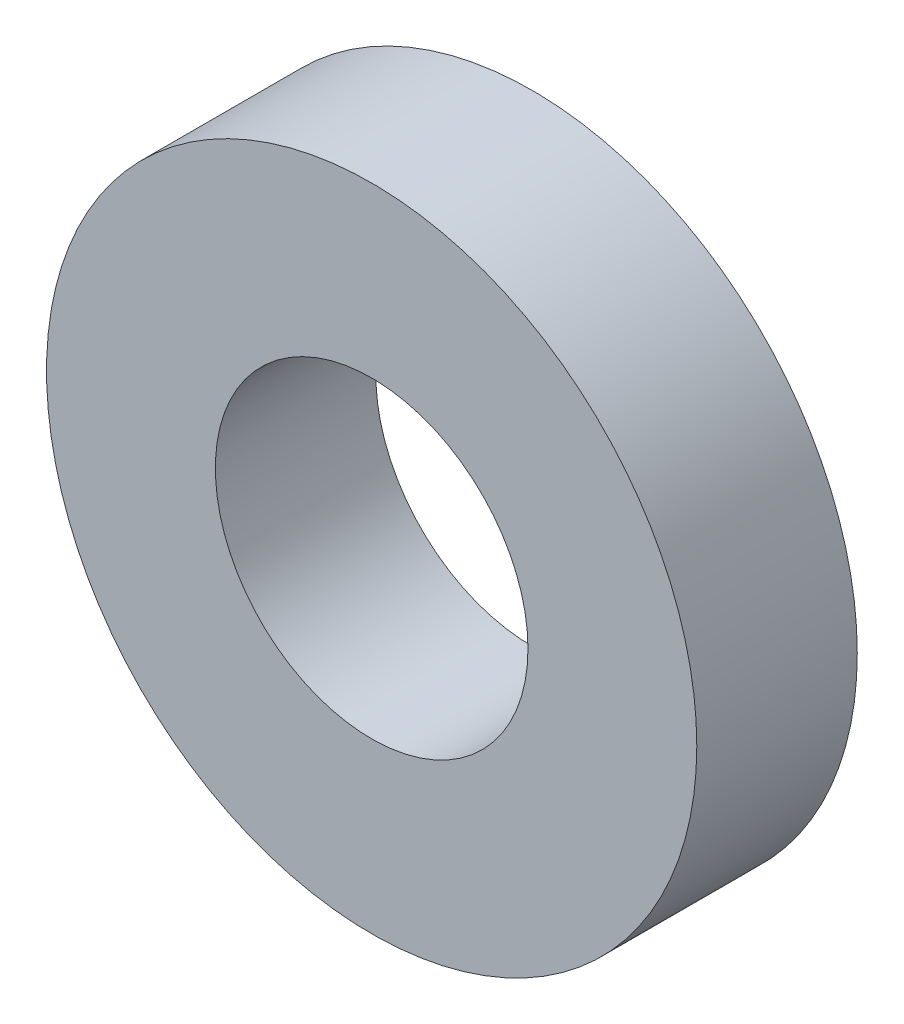
SolidWorks part; units mm, degrees
ref_plane "Front Plane" through (0, 0, 0) normal (0, 0, 1) x (1, 0, 0)
ref_plane "Top Plane" through (0, 0, 0) normal (0, 1, 0) x (1, 0, 0)
ref_plane "Right Plane" through (0, 0, 0) normal (1, 0, 0) x (0, 0, -1)
sketch "Sketch1" plane through (0, 0, 0) normal (0, 0, 1) x (1, 0, 0)
  circle A0 centre (0, 0) radius 1.905
  circle A1 centre (0, 0) radius 3.9624
  dimension "ID" = 3.81
  dimension "OD" = 7.9248
extrude "Extrude1" add sketch "Sketch1" against normal blind 1.9558
